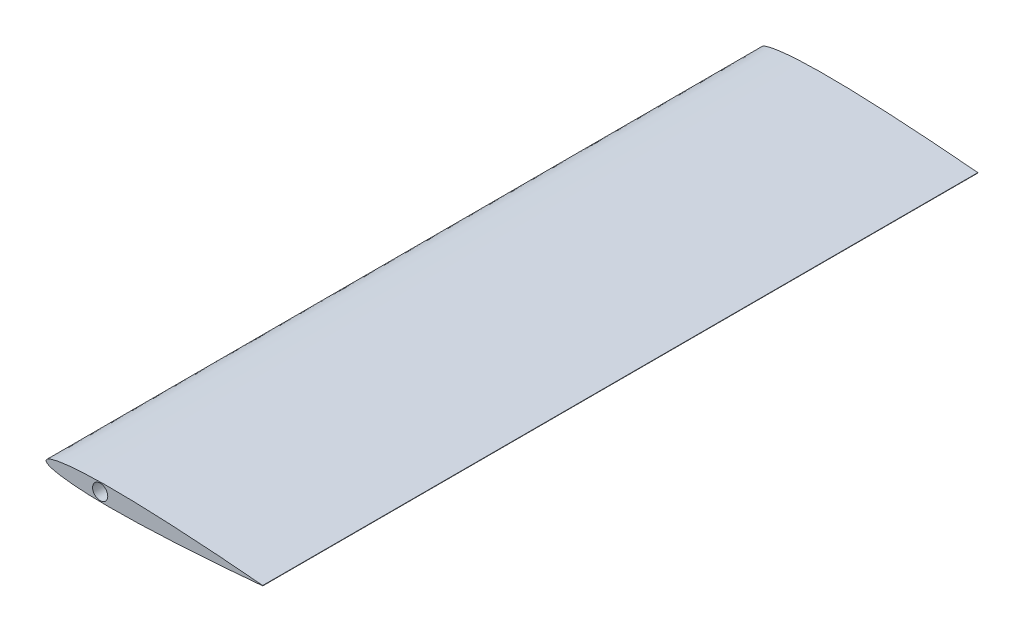
SolidWorks part; units mm, degrees
material "Foam"
ref_plane "Piano frontale" through (0, 0, 0) normal (0, 0, 1) x (1, 0, 0)
ref_plane "Piano superiore" through (0, 0, 0) normal (0, 1, 0) x (1, 0, 0)
ref_plane "Piano destro" through (0, 0, 0) normal (1, 0, 0) x (0, 0, -1)
curve "Curva1"
  spline degree 3 poles (100, 0.084, 0) (98.3335, 0.2367, 0) (95.0012, 0.5422, 0) (88.3356, 1.1109, 0) (80.0033, 1.7636, 0) (70.003, 2.4579, 0) (60.0031, 3.0617, 0) (50.003, 3.5521, 0) (40.0026, 3.9029, 0) (31.667, 4.0253, 0) (24.9992, 3.9769, 0) (19.9978, 3.845, 0) (14.9934, 3.5925, 0) (10.8272, 3.2377, 0) (7.4891, 2.814, 0) (4.9936, 2.4037, 0) (2.8496, 1.8679, 0) (1.1654, 1.321, 0) (-0.6646, 0, 0) (1.1654, -1.321, 0) (2.8496, -1.8679, 0) (4.9936, -2.4037, 0) (7.4891, -2.814, 0) (10.8272, -3.2377, 0) (14.9934, -3.5925, 0) (19.9978, -3.845, 0) (24.9992, -3.9769, 0) (31.667, -4.0253, 0) (40.0026, -3.9029, 0) (50.003, -3.5521, 0) (60.0031, -3.0617, 0) (70.003, -2.4579, 0) (80.0033, -1.7636, 0) (88.3356, -1.1109, 0) (95.0012, -0.5422, 0) (98.3335, -0.2367, 0) (100, -0.084, 0) knots 0 0 0 0 0.024876 0.049742 0.099443 0.149112 0.198751 0.248359 0.297937 0.347491 0.372267 0.397051 0.421859 0.446731 0.45922 0.471791 0.48456 0.491195 0.5 0.508805 0.51544 0.528209 0.54078 0.553269 0.578141 0.602949 0.627733 0.652509 0.702063 0.751641 0.801249 0.850888 0.900557 0.950258 0.975124 1 1 1 1
sketch "Schizzo2" plane through (0, 0, 0) normal (0, 0, 1) x (1, 0, 0)
  arc A0 (100, 0.084) -> (100, -0.084) centre (99.9923, 0) cw
  spline S0 degree 3 poles (633.0503, 1915.9881) (335.6221, -48.8321) (214.9188, -9.6895) (88.3356, 1.1109) (80.0033, 1.7636) (70.003, 2.4579) (60.0031, 3.0617) (50.003, 3.5521) (40.0026, 3.9029) (31.667, 4.0253) (24.9992, 3.9769) (19.9978, 3.845) (14.9934, 3.5925) (10.8272, 3.2377) (7.4891, 2.814) (4.9936, 2.4037) (2.8496, 1.8679) (1.1654, 1.321) (-0.6646, 0) (1.1654, -1.321) (2.8496, -1.8679) (4.9936, -2.4037) (7.4891, -2.814) (10.8272, -3.2377) (14.9934, -3.5925) (19.9978, -3.845) (24.9992, -3.9769) (31.667, -4.0253) (40.0026, -3.9029) (50.003, -3.5521) (60.0031, -3.0617) (70.003, -2.4579) (80.0033, -1.7636) (88.3356, -1.1109) (214.9185, 9.6894) (335.6215, 48.8319) (633.0478, -1915.9718) knots -1.78903 -1.78903 -1.78903 -1.78903 0.024876 0.049742 0.099443 0.149112 0.198751 0.248359 0.297937 0.347491 0.372267 0.397051 0.421859 0.446731 0.45922 0.471791 0.48456 0.491195 0.5 0.508805 0.51544 0.528209 0.54078 0.553269 0.578141 0.602949 0.627733 0.652509 0.702063 0.751641 0.801249 0.850888 0.900557 0.950258 0.975124 2.789025 2.789025 2.789025 2.789025 only from (100, 0.084) to (100, -0.084) construction
  spline S1 degree 3 poles (100, 0.084) (98.3335, 0.2367) (95.0012, 0.5422) (88.3356, 1.1109) (80.0033, 1.7636) (70.003, 2.4579) (60.0031, 3.0617) (50.003, 3.5521) (40.0026, 3.9029) (31.667, 4.0253) (24.9992, 3.9769) (19.9978, 3.845) (14.9934, 3.5925) (10.8272, 3.2377) (7.4891, 2.814) (4.9936, 2.4037) (2.8496, 1.8679) (1.1654, 1.321) (-0.6646, 0) (1.1654, -1.321) (2.8496, -1.8679) (4.9936, -2.4037) (7.4891, -2.814) (10.8272, -3.2377) (14.9934, -3.5925) (19.9978, -3.845) (24.9992, -3.9769) (31.667, -4.0253) (40.0026, -3.9029) (50.003, -3.5521) (60.0031, -3.0617) (70.003, -2.4579) (80.0033, -1.7636) (88.3356, -1.1109) (95.0012, -0.5422) (98.3335, -0.2367) (100, -0.084) knots 0 0 0 0 0.024876 0.049742 0.099443 0.149112 0.198751 0.248359 0.297937 0.347491 0.372267 0.397051 0.421859 0.446731 0.45922 0.471791 0.48456 0.491195 0.5 0.508805 0.51544 0.528209 0.54078 0.553269 0.578141 0.602949 0.627733 0.652509 0.702063 0.751641 0.801249 0.850888 0.900557 0.950258 0.975124 1 1 1 1
extrude "Estrusione-Estrusione1" add sketch "Schizzo2" along normal blind 330
sketch "Schizzo3" plane through (0, 0, 330) normal (0, 0, 1) x (1, 0, 0)
  circle A0 centre (25, 0) radius 3
  dimension "D1" = 6
  dimension "D2" = 25
extrude "Taglio-Estrusione1" cut sketch "Schizzo3" against normal through all
sketch "Schizzo4" plane through (0, 0, 330) normal (0, 0, 1) x (1, 0, 0)
  circle A0 centre (25, 0) radius 3.5
  circle A1 centre (25, 0) radius 3
  circle A2 centre (25, 0) radius 3 construction
  dimension "D1" = 7
extrude "Taglio-Estrusione2" cut sketch "Schizzo4" against normal blind 20
